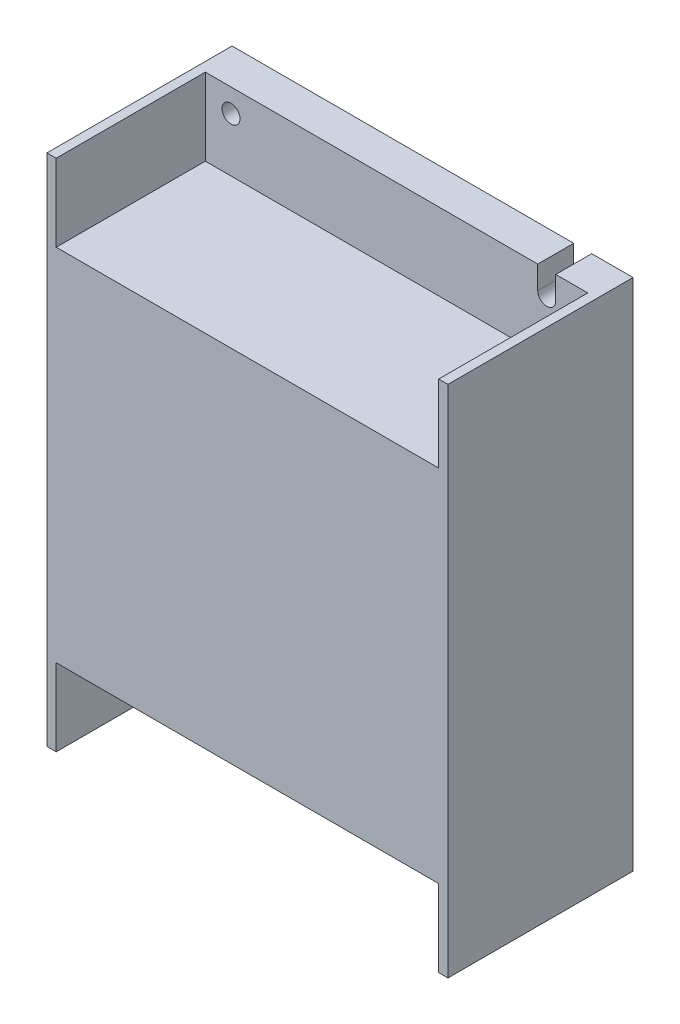
SolidWorks part; units mm, degrees
ref_plane "前视基准面" through (0, 0, 0) normal (0, 0, 1) x (1, 0, 0)
ref_plane "上视基准面" through (0, 0, 0) normal (0, 1, 0) x (1, 0, 0)
ref_plane "右视基准面" through (0, 0, 0) normal (1, 0, 0) x (0, 0, -1)
sketch "草图1" plane through (0, 0, 0) normal (0, 0, 1) x (1, 0, 0)
  line L1 (-39, 50) -> (39, 50)
  line L2 (-39, 50) -> (-39, -50)
  line L3 (-39, -50) -> (39, -50)
  line L4 (39, 50) -> (39, -50)
  line L5 (-39, 50) -> (39, -50) construction
  line L6 (-39, -50) -> (39, 50) construction
  point P0 (0, 0)
  dimension "D1" = 78
  dimension "D2" = 100
extrude "凸台-拉伸1" add sketch "草图1" along normal blind 36
sketch "草图2" plane through (0, 0, 36) normal (0, 0, 1) x (1, 0, 0)
  line L0 (39, -50) -> (39, 50) construction
  line L2 (39, 50) -> (-39, 50) construction
  line L3 (-37.2, 50) -> (37.2, 50)
  line L4 (-37.2, 50) -> (-37.2, 35)
  line L5 (-37.2, 35) -> (37.2, 35)
  line L6 (37.2, 50) -> (37.2, 35)
  line L8 (-39, 50) -> (-39, -50) construction
  dimension "D1" = 1.8
  dimension "D2" = 15
  dimension "D3" = 1.8
extrude "切除-拉伸1" cut sketch "草图2" against normal offset from surface (29 mm away) 7 up to face at (0, 0, 0)
sketch "草图4" plane through (0, 0, 0) normal (0, 0, -1) x (-1, 0, 0)
  line L0 (27.4645, -45.5) -> (27.4645, -50)
  line L1 (32.1994, 45.5) -> (-29.2145, 45.5) construction
  line L2 (-48.0648, 0) -> (44.0202, 0) construction
  line L3 (0, 80.4418) -> (0, -76.2597) construction
  line L4 (27.4645, -50) -> (30.9645, -50)
  line L5 (37.2, 50) -> (-37.2, 50) construction
  line L6 (30.9645, -50) -> (30.9645, -45.5)
  line L7 (-27.4645, 45.5) -> (-27.4645, 50)
  line L8 (-27.4645, 50) -> (-30.9645, 50)
  line L9 (-30.9645, 50) -> (-30.9645, 45.5)
  line L10 (-32.1994, -45.5) -> (29.2145, -45.5) construction
  line L11 (48.0648, 0) -> (-44.0202, 0) construction
  circle A0 centre (-32.1994, -45.5) radius 1.75
  circle A1 centre (32.1994, 45.5) radius 1.75
  arc A2 (27.4645, -45.5) -> (30.9645, -45.5) centre (29.2145, -45.5) cw
  arc A4 (-27.4645, 45.5) -> (-30.9645, 45.5) centre (-29.2145, 45.5) cw
  point P0 (0, 0)
  point P27 (0, 0)
  dimension "D5" = 3.5
  dimension "D6" = 1.75
  dimension "D1" = 2
  dimension "D4" = 4.5
extrude "切除-拉伸2" cut sketch "草图4" against normal blind 10
mirror "镜向1" about plane through (0, 0, 0) normal (0, 1, 0) of "切除-拉伸1"
